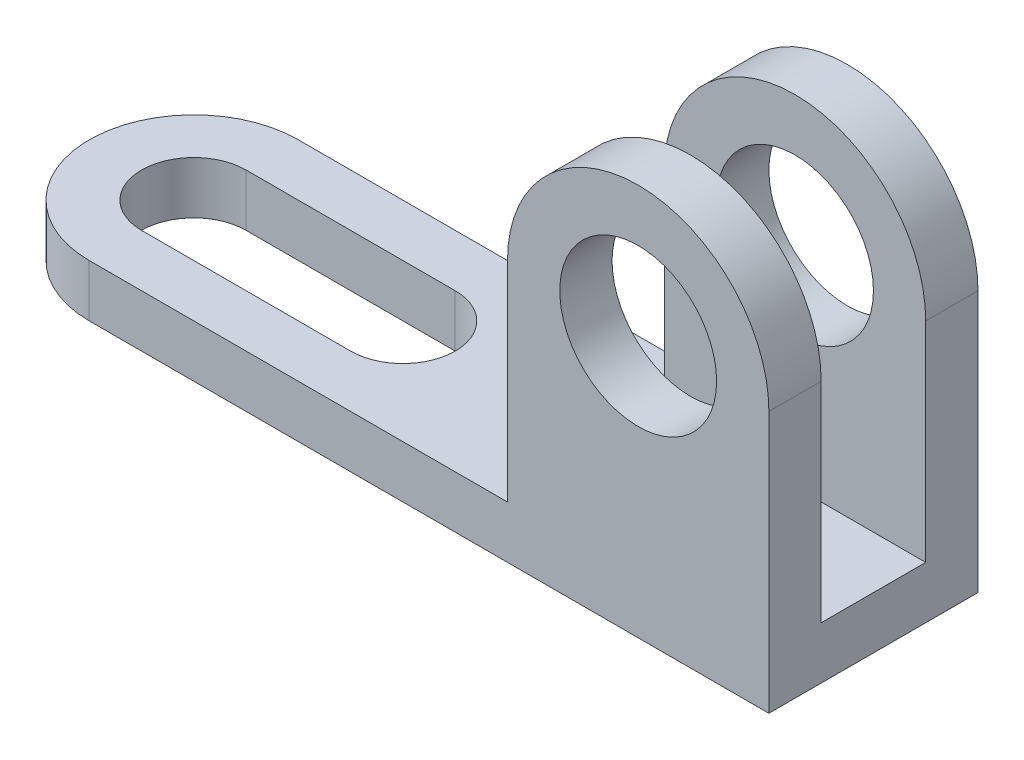
SolidWorks part; units mm, degrees
ref_plane "Front Plane" through (0, 0, 0) normal (0, 0, 1) x (1, 0, 0)
ref_plane "Top Plane" through (0, 0, 0) normal (0, 1, 0) x (1, 0, 0)
ref_plane "Right Plane" through (0, 0, 0) normal (1, 0, 0) x (0, 0, -1)
sketch "Sketch1" plane through (0, 0, 0) normal (0, 1, 0) x (1, 0, 0)
  line L0 (-25, 0) -> (-65, 0) construction
  line L1 (-65, 20) -> (65, 20)
  line L3 (-65, -20) -> (65, -20)
  line L4 (65, 20) -> (65, -20)
  line L5 (-65, 20) -> (65, -20) construction
  line L6 (-65, -20) -> (65, 20) construction
  line L7 (-25, -10) -> (-65, -10)
  line L8 (-25, 10) -> (-65, 10)
  line L9 (65, 0) -> (0, 0) construction
  line L10 (15, -10) -> (65, -10)
  line L11 (15, -10) -> (15, -20)
  line L12 (15, -20) -> (65, -20)
  line L13 (65, -10) -> (65, -20)
  line L14 (15, -10) -> (65, -20) construction
  line L15 (15, -20) -> (65, -10) construction
  line L16 (15, 20) -> (65, 20)
  line L17 (65, 10) -> (65, 20)
  line L18 (15, 10) -> (65, 10)
  line L19 (15, 10) -> (15, 20)
  arc A0 (-25, -10) -> (-25, 10) centre (-25, 0) ccw
  arc A1 (-65, 10) -> (-65, -10) centre (-65, 0) ccw
  arc A2 (-65, 20) -> (-65, -20) centre (-65, 0) ccw
  point P0 (0, 0)
  point P8 (-45, 0)
  point P14 (40, -15)
  dimension "D5" = 10
  dimension "D6" = 10
  dimension "D1" = 130
  dimension "D2" = 40
  dimension "D3" = 90
  dimension "D4" = 40
  dimension "D7" = 50
extrude "Boss-Extrude1" add sketch "Sketch1" along normal blind 10 contours L1 A2 L3 L11 L10 L4 L18 L19 A1 L8 A0 L7
sketch "Sketch2" plane through (0, 10, 0) normal (0, 1, 0) x (1, 0, 0)
  line L0 (15, -20) -> (15, -10)
  line L1 (15, -10) -> (65, -10)
  line L2 (15, -20) -> (65, -20)
  line L3 (65, -20) -> (65, -10)
  line L4 (15, 20) -> (15, 10)
  line L5 (15, 10) -> (65, 10)
  line L6 (65, 10) -> (65, 20)
  line L7 (65, 20) -> (15, 20)
extrude "Boss-Extrude2" add sketch "Sketch2" along normal blind 40 and the other way up to surface (10 mm away) other way up to face at (-45, 0, 0)
sketch "Sketch3" plane through (0, 0, 20) normal (0, 0, 1) x (1, 0, 0)
  line L0 (15, 50) -> (65, 50) construction
  circle A0 centre (40, 50) radius 25
extrude "Boss-Extrude3" add sketch "Sketch3" against normal up to surface (10 mm away) up to face at (40, 30, 10)
sketch "Sketch4" plane through (0, 0, -20) normal (0, 0, -1) x (-1, 0, 0)
  line L0 (-65, 50) -> (-15, 50) construction
  circle A0 centre (-40, 50) radius 25
extrude "Boss-Extrude4" add sketch "Sketch4" against normal up to surface (10 mm away) up to face at (40, 30, -10)
sketch "Sketch5" plane through (0, 0, 20) normal (0, 0, 1) x (1, 0, 0)
  circle A0 centre (40, 50) radius 15
  dimension "D1" = 30
extrude "Cut-Extrude1" cut sketch "Sketch5" against normal up to surface (40 mm away)
